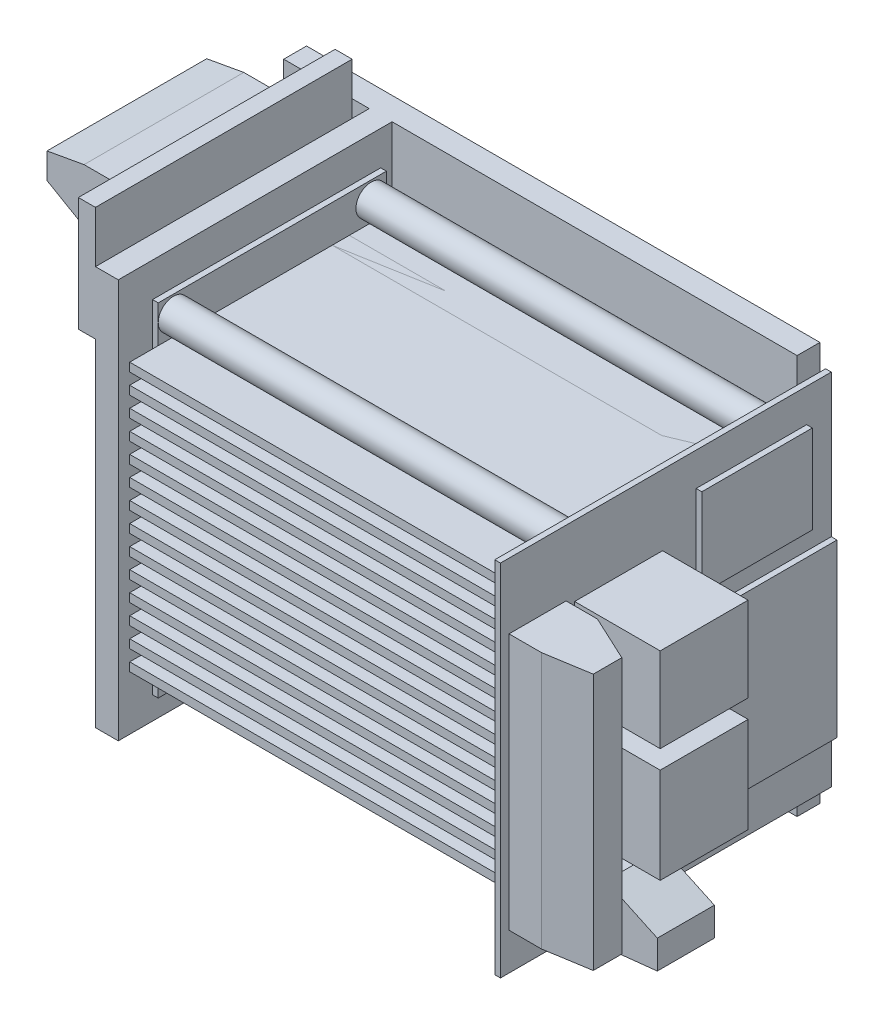
SolidWorks part; units mm, degrees
ref_plane "Front Plane" through (0, 0, 0) normal (0, 0, 1) x (1, 0, 0)
ref_plane "Top Plane" through (0, 0, 0) normal (0, 1, 0) x (1, 0, 0)
ref_plane "Right Plane" through (0, 0, 0) normal (1, 0, 0) x (0, 0, -1)
ref_plane "Plane1" through (0, 0, 0) normal (0, 0, 1) x (1, 0, 0)
ref_plane "Plane2" through (0, 0, 0) normal (0, 1, 0) x (1, 0, 0)
ref_plane "Plane3" through (0, 0, 0) normal (1, 0, 0) x (0, 0, -1)
sketch "Sketch2" plane through (0, 0, 0) normal (0, 0, 1) x (1, 0, 0)
  line L1 (0, 0) -> (90, 0)
  line L2 (0, 0) -> (0, 70)
  line L3 (0, 70) -> (90, 70)
  line L4 (90, 0) -> (90, 70)
  dimension "D1" = 90
  dimension "D2" = 70
extrude "Boss-Extrude1" add sketch "Sketch2" along normal blind 4
ref_plane "Plane4" through (15, 0, 0) normal (1, 0, 0) x (0, 0, -1)
sketch "Sketch3" plane through (0, 0, 0) normal (0, 0, 1) x (1, 0, 0)
  line L0 (15, -2.2) -> (15, 2.2) construction
  line L1 (15, 70) -> (19, 70)
  line L2 (15, 70) -> (15, 0)
  line L3 (15, 0) -> (19, 0)
  line L4 (19, 70) -> (19, 0)
  line L5 (90, 70) -> (0, 70) construction
  line L6 (2.2, 0) -> (-2.2, 0) construction
  dimension "D1" = 4
extrude "Boss-Extrude2" add sketch "Sketch3" along normal blind 52
sketch "Sketch4" plane through (15, 0, 0) normal (1, 0, 0) x (0, 0, -1)
  line L0 (-52, 70) -> (-52, 0) construction
  line L5 (-52, 59) -> (-7, 59)
  line L6 (-52, 59) -> (-52, 79)
  line L7 (-52, 79) -> (-7, 79)
  line L8 (-7, 59) -> (-7, 79)
  line L9 (-52, 70) -> (-4, 70) construction
  dimension "D1" = 45
  dimension "D2" = 20
  dimension "D3" = 0
  dimension "D4" = 9
extrude "Boss-Extrude3" add sketch "Sketch4" against normal blind 3 separate body
ref_plane "Plane5" through (0, 0, 45) normal (0, 0, 1) x (1, 0, 0)
sketch "Sketch5" plane through (0, 0, 45) normal (0, 0, 1) x (1, 0, 0)
  line L0 (12, 77.4896) -> (12, 67.4896)
  line L1 (12, 79) -> (12, 59) construction
  line L2 (12, 67.4896) -> (7, 67.4896)
  line L3 (7, 67.4896) -> (-0.5, 71.8198)
  line L4 (-0.5, 71.8198) -> (-0.5, 76.3198)
  line L5 (-0.5, 76.3198) -> (6, 77.4896)
  line L6 (6, 77.4896) -> (12, 77.4896)
  dimension "D1" = 10
  dimension "D2" = 5
  dimension "D3" = 7.5
  dimension "D4" = 150
  dimension "D5" = 4.5
  dimension "D6" = 6
extrude "Boss-Extrude4" add sketch "Sketch5" against normal blind 28
ref_plane "Plane6" through (20, 0, 0) normal (1, 0, 0) x (0, 0, -1)
sketch "Sketch6" plane through (20, 0, 0) normal (1, 0, 0) x (0, 0, -1)
  line L0 (28.6, 0) -> (-28.6, 0) construction
  line L1 (-47, 5) -> (-7, 5)
  line L2 (-47, 5) -> (-47, 65)
  line L3 (-47, 65) -> (-7, 65)
  line L4 (-7, 5) -> (-7, 65)
  line L5 (-52, 0) -> (-52, 70) construction
  dimension "D1" = 40
  dimension "D2" = 60
  dimension "D3" = 5
  dimension "D4" = 5
extrude "Boss-Extrude5" add sketch "Sketch6" along normal blind 1 separate body
ref_plane "Plane7" through (21, 0, 0) normal (1, 0, 0) x (0, 0, -1)
sketch "Sketch7" plane through (21, 0, 0) normal (1, 0, 0) x (0, 0, -1)
  line L0 (-47, 35) -> (-7, 35) construction
  line L1 (-47, 65) -> (-47, 5) construction
  line L2 (-7, 5) -> (-7, 65) construction
  line L3 (-27, 35) -> (-27, 65) construction
  line L4 (-7, 65) -> (-47, 65) construction
  circle A0 centre (-44.3298, 7.9999) radius 2.6702
  circle A1 centre (-44.3298, 62.0001) radius 2.6702
  circle A2 centre (-9.6702, 62.0001) radius 2.6702
  circle A3 centre (-9.6702, 7.9999) radius 2.6702
extrude "Boss-Extrude6" add sketch "Sketch7" along normal blind 70
sketch "Sketch8" plane through (21, 0, 0) normal (1, 0, 0) x (0, 0, -1)
  line L0 (-47, 62.0001) -> (-47, 7.9999) construction
  line L1 (-13.5, 11.5) -> (-40.5, 11.5)
  line L2 (-13.5, 11.5) -> (-13.5, 58.5)
  line L3 (-13.5, 58.5) -> (-40.5, 58.5)
  line L4 (-40.5, 11.5) -> (-40.5, 58.5)
  line L5 (-7, 7.9999) -> (-7, 62.0001) construction
  line L6 (-47, 5) -> (-7, 5) construction
  line L7 (-7, 65) -> (-47, 65) construction
  dimension "D1" = 6.5
  dimension "D2" = 6.5
  dimension "6.5" = 6.5
  dimension "D4" = 6.5
extrude "Boss-Extrude7" add sketch "Sketch8" along normal blind 65
sketch "Sketch10" plane through (21, 0, 0) normal (1, 0, 0) x (0, 0, -1)
  line L2 (-52, 0) -> (-52, 70) construction
  line L9 (-45, 43.45) -> (-45, -43.45) construction
  line L27 (-45, 16.5) -> (-52, 16.5)
  line L28 (-52, 16.5) -> (-52, 15)
  line L29 (-52, 15) -> (-45, 15)
  line L30 (-45, 15) -> (-45, 13)
  line L31 (-45, 13) -> (-52, 13)
  line L32 (-40.5, 11.5) -> (-52, 11.5)
  line L33 (-52, 11.5) -> (-52, 13)
  line L34 (-45, 16.5) -> (-45, 18.5)
  line L35 (-45, 18.5) -> (-52, 18.5)
  line L36 (-52, 18.5) -> (-52, 20)
  line L37 (-52, 20) -> (-45, 20)
  line L38 (-45, 20) -> (-45, 22)
  line L39 (-45, 22) -> (-52, 22)
  line L40 (-52, 22) -> (-52, 23.5)
  line L41 (-52, 23.5) -> (-45, 23.5)
  line L42 (-45, 23.5) -> (-45, 25.5)
  line L43 (-45, 25.5) -> (-52, 25.5)
  line L44 (-52, 25.5) -> (-52, 27)
  line L45 (-52, 27) -> (-45, 27)
  line L46 (-45, 27) -> (-45, 29)
  line L47 (-45, 29) -> (-52, 29)
  line L48 (-52, 29) -> (-52, 30.5)
  line L49 (-52, 30.5) -> (-45, 30.5)
  line L50 (-45, 30.5) -> (-45, 32.5)
  line L51 (-47, 35) -> (-10, 35) construction
  line L52 (-47, 62.0001) -> (-47, 7.9999) construction
  line L53 (-28.5, 35) -> (-28.5, 66.0339) construction
  line L54 (-45, 32.5) -> (-52, 32.5)
  line L55 (-52, 32.5) -> (-52, 34)
  line L56 (-52, 34) -> (-45, 34)
  line L57 (-45, 34) -> (-45, 36)
  line L58 (-52, 36) -> (-45, 36)
  line L59 (-52, 37.5) -> (-52, 36)
  line L60 (-45, 37.5) -> (-52, 37.5)
  line L61 (-45, 39.5) -> (-45, 37.5)
  line L62 (-52, 39.5) -> (-45, 39.5)
  line L63 (-52, 41) -> (-52, 39.5)
  line L64 (-45, 41) -> (-52, 41)
  line L65 (-45, 43) -> (-45, 41)
  line L66 (-52, 43) -> (-45, 43)
  line L67 (-52, 44.5) -> (-52, 43)
  line L68 (-45, 44.5) -> (-52, 44.5)
  line L69 (-45, 46.5) -> (-45, 44.5)
  line L70 (-52, 46.5) -> (-45, 46.5)
  line L71 (-52, 48) -> (-52, 46.5)
  line L72 (-45, 48) -> (-52, 48)
  line L73 (-45, 50) -> (-45, 48)
  line L74 (-52, 50) -> (-45, 50)
  line L75 (-52, 51.5) -> (-52, 50)
  line L76 (-45, 51.5) -> (-52, 51.5)
  line L77 (-45, 53.5) -> (-45, 51.5)
  line L78 (-52, 58.5) -> (-52, 57)
  line L79 (-40.5, 58.5) -> (-52, 58.5)
  line L80 (-45, 57) -> (-52, 57)
  line L81 (-45, 55) -> (-45, 57)
  line L82 (-52, 55) -> (-45, 55)
  line L83 (-52, 53.5) -> (-52, 55)
  line L84 (-45, 53.5) -> (-52, 53.5)
  line L85 (-40.5, 11.5) -> (-40.5, 58.5)
  line L86 (-16.5, 11.5) -> (-16.5, 58.5)
  line L87 (-12, 53.5) -> (-5, 53.5)
  line L88 (-5, 53.5) -> (-5, 55)
  line L89 (-5, 55) -> (-12, 55)
  line L90 (-12, 55) -> (-12, 57)
  line L91 (-12, 57) -> (-5, 57)
  line L92 (-16.5, 58.5) -> (-5, 58.5)
  line L93 (-5, 58.5) -> (-5, 57)
  line L94 (-12, 53.5) -> (-12, 51.5)
  line L95 (-12, 51.5) -> (-5, 51.5)
  line L96 (-5, 51.5) -> (-5, 50)
  line L97 (-5, 50) -> (-12, 50)
  line L98 (-12, 50) -> (-12, 48)
  line L99 (-12, 48) -> (-5, 48)
  line L100 (-5, 48) -> (-5, 46.5)
  line L101 (-5, 46.5) -> (-12, 46.5)
  line L102 (-12, 46.5) -> (-12, 44.5)
  line L103 (-12, 44.5) -> (-5, 44.5)
  line L104 (-5, 44.5) -> (-5, 43)
  line L105 (-5, 43) -> (-12, 43)
  line L106 (-12, 43) -> (-12, 41)
  line L107 (-12, 41) -> (-5, 41)
  line L108 (-5, 41) -> (-5, 39.5)
  line L109 (-5, 39.5) -> (-12, 39.5)
  line L110 (-12, 39.5) -> (-12, 37.5)
  line L111 (-12, 37.5) -> (-5, 37.5)
  line L112 (-5, 37.5) -> (-5, 36)
  line L113 (-5, 36) -> (-12, 36)
  line L114 (-12, 34) -> (-12, 36)
  line L115 (-5, 34) -> (-12, 34)
  line L116 (-5, 32.5) -> (-5, 34)
  line L117 (-12, 32.5) -> (-5, 32.5)
  line L118 (-12, 30.5) -> (-12, 32.5)
  line L119 (-5, 30.5) -> (-12, 30.5)
  line L120 (-5, 29) -> (-5, 30.5)
  line L121 (-12, 29) -> (-5, 29)
  line L122 (-12, 27) -> (-12, 29)
  line L123 (-5, 27) -> (-12, 27)
  line L124 (-5, 25.5) -> (-5, 27)
  line L125 (-12, 25.5) -> (-5, 25.5)
  line L126 (-12, 23.5) -> (-12, 25.5)
  line L127 (-5, 23.5) -> (-12, 23.5)
  line L128 (-5, 22) -> (-5, 23.5)
  line L129 (-12, 22) -> (-5, 22)
  line L130 (-12, 20) -> (-12, 22)
  line L131 (-5, 20) -> (-12, 20)
  line L132 (-5, 18.5) -> (-5, 20)
  line L133 (-12, 18.5) -> (-5, 18.5)
  line L134 (-12, 16.5) -> (-12, 18.5)
  line L135 (-5, 11.5) -> (-5, 13)
  line L136 (-16.5, 11.5) -> (-5, 11.5)
  line L137 (-12, 13) -> (-5, 13)
  line L138 (-12, 15) -> (-12, 13)
  line L139 (-5, 15) -> (-12, 15)
  line L140 (-5, 16.5) -> (-5, 15)
  line L141 (-12, 16.5) -> (-5, 16.5)
  point P42 (-45, 35)
  point P124 (-12, 35)
  dimension "D1" = 1.5
  dimension "D2" = 2
  dimension "2" = 2
  dimension "D3" = 1.5
  dimension "D4" = 12
extrude "Boss-Extrude8" add sketch "Sketch10" along normal blind 65 separate body
ref_plane "Plane8" through (91, 0, 0) normal (1, 0, 0) x (0, 0, -1)
sketch "Sketch11" plane through (91, 0, 0) normal (1, 0, 0) x (0, 0, -1)
  line L0 (0, 43.45) -> (0, -43.45) construction
  line L1 (-58, 3.4999) -> (0, 3.4999)
  line L2 (-58, 3.4999) -> (-58, 66.4999)
  line L3 (-58, 66.4999) -> (0, 66.4999)
  line L4 (0, 3.4999) -> (0, 66.4999)
  circle A0 centre (-44.3298, 7.9999) radius 2.6702 construction
  dimension "D4" = 4.5
  dimension "D1" = 63
  dimension "D2" = 58
  dimension "D3" = 0
extrude "Boss-Extrude9" add sketch "Sketch11" along normal blind 1
ref_plane "Plane9" through (0, 10, 0) normal (0, 1, 0) x (1, 0, 0)
sketch "Sketch13" plane through (0, 10, 0) normal (0, 1, 0) x (1, 0, 0)
  line L0 (92, -56.5) -> (92, -46.5)
  line L1 (92, -58) -> (92, 0) construction
  line L2 (92, -46.5) -> (97.5, -46.5)
  line L3 (97.5, -46.5) -> (105.5, -50.2305)
  line L4 (105.5, -50.2305) -> (105.5, -55.2305)
  line L5 (105.5, -55.2305) -> (97.683, -56.5)
  line L6 (97.683, -56.5) -> (92, -56.5)
  line L8 (92, -58) -> (91, -58) construction
  dimension "D1" = 155
  dimension "D2" = 10
  dimension "D3" = 1.5
  dimension "D4" = 5
  dimension "D5" = 5.5
  dimension "D6" = 8
extrude "Boss-Extrude10" add sketch "Sketch13" along normal blind 45 separate body
ref_plane "Plane10" through (92, 0, 0) normal (1, 0, 0) x (0, 0, -1)
sketch "Sketch14" plane through (92, 0, 0) normal (1, 0, 0) x (0, 0, -1)
  line L0 (-45, 43.45) -> (-45, -43.45) construction
  line L1 (-45, 39.319) -> (-29.5884, 39.319)
  line L2 (-45, 39.319) -> (-45, 54.1638)
  line L3 (-45, 54.1638) -> (-29.5884, 54.1638)
  line L4 (-29.5884, 39.319) -> (-29.5884, 54.1638)
  line L6 (-45, 19.3146) -> (-29.5884, 19.3146)
  line L7 (-45, 19.3146) -> (-45, 36.0603)
  line L8 (-45, 36.0603) -> (-29.5884, 36.0603)
  line L9 (-29.5884, 19.3146) -> (-29.5884, 36.0603)
extrude "Boss-Extrude11" add sketch "Sketch14" along normal blind 15 separate body
sketch "Sketch15" plane through (0, 0, 45) normal (0, 0, 1) x (1, 0, 0)
  line L0 (92, 4.4999) -> (92, 14.4999)
  line L1 (92, -31.9) -> (92, 31.9) construction
  line L2 (92, 14.4999) -> (97.5, 14.4999)
  line L3 (97.5, 14.4999) -> (106.5, 10.3031)
  line L4 (106.5, 10.3031) -> (106.5, 5.3031)
  line L5 (106.5, 5.3031) -> (99, 4.4999)
  line L6 (99, 4.4999) -> (92, 4.4999)
  line L7 (92, 3.4999) -> (91, 3.4999) construction
  dimension "D1" = 10
  dimension "D2" = 1
  dimension "D3" = 5.5
  dimension "D4" = 9
  dimension "D5" = 7
  dimension "D6" = 5
  dimension "D7" = 155
extrude "Boss-Extrude12" add sketch "Sketch15" against normal blind 10
ref_plane "Plane11" through (94, 0, 0) normal (1, 0, 0) x (0, 0, -1)
sketch "Sketch16" plane through (94, 0, 0) normal (1, 0, 0) x (0, 0, -1)
  line L0 (0, 43.45) -> (0, -43.45) construction
  line L1 (-2, 43.4999) -> (-22, 43.4999)
  line L2 (-2, 43.4999) -> (-2, 13.4999)
  line L3 (-2, 13.4999) -> (-22, 13.4999)
  line L4 (-22, 43.4999) -> (-22, 13.4999)
  line L5 (-58, 3.4999) -> (0, 3.4999) construction
  dimension "D1" = 2
  dimension "D2" = 20
  dimension "D3" = 10
  dimension "D4" = 30
extrude "Boss-Extrude13" add sketch "Sketch16" along normal blind 1 separate body
sketch "Sketch18" plane through (94, 0, 0) normal (1, 0, 0) x (0, 0, -1)
  line L1 (-6.3254, 62.6725) -> (-25.6961, 62.6725)
  line L2 (-6.3254, 62.6725) -> (-6.3254, 47.194)
  line L3 (-6.3254, 47.194) -> (-25.6961, 47.194)
  line L4 (-25.6961, 62.6725) -> (-25.6961, 47.194)
extrude "Boss-Extrude14" add sketch "Sketch18" along normal blind 1 separate body
